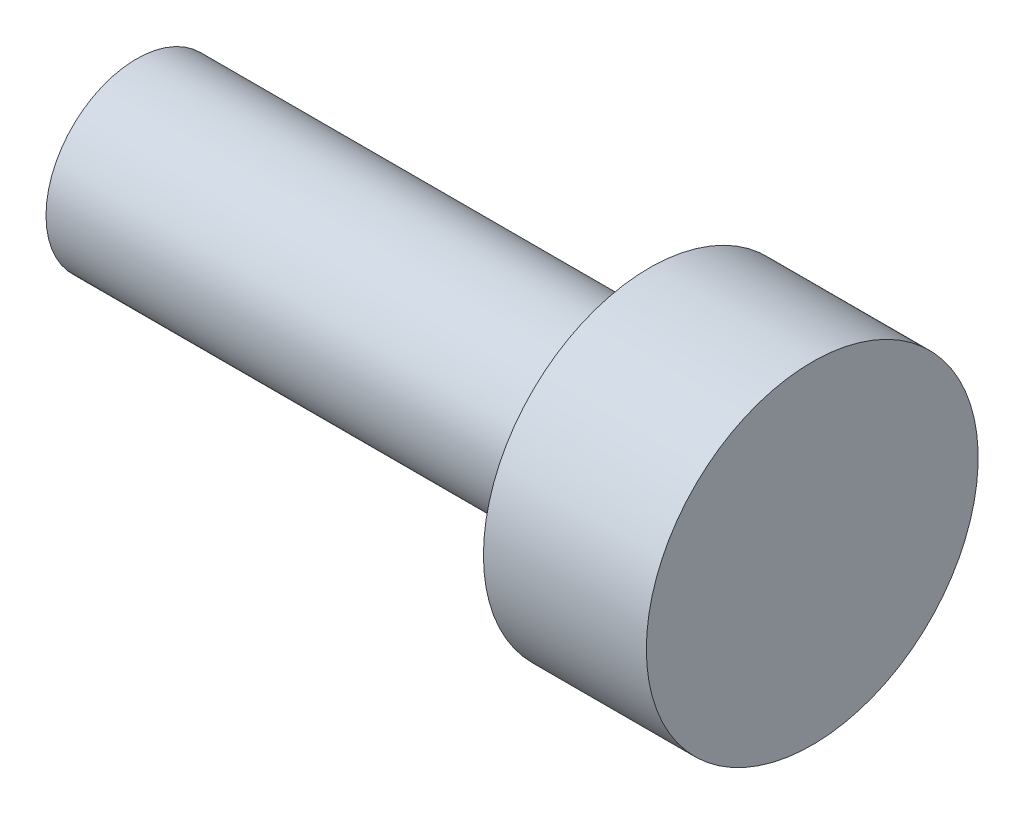
SolidWorks part; units mm, degrees
material "AISI Type 316L stainless steel"
ref_plane "Front Plane" through (0, 0, 0) normal (0, 0, 1) x (1, 0, 0)
ref_plane "Top Plane" through (0, 0, 0) normal (0, 1, 0) x (1, 0, 0)
ref_plane "Right Plane" through (0, 0, 0) normal (1, 0, 0) x (0, 0, -1)
sketch "Axial profile (mm)" plane through (0, 0, 0) normal (0, 0, 1) x (1, 0, 0)
  line L0 (-110, 0) -> (75, 0) construction
  line L1 (165.5, 0) -> (176.7, 0)
  line L2 (176.7, 0) -> (176.7, 2.75)
  line L3 (176.7, 2.75) -> (174, 2.75)
  line L4 (174, 2.75) -> (174, 1.5)
  line L5 (174, 1.5) -> (165.5, 1.5)
  line L6 (165.5, 1.5) -> (165.5, 0)
revolve "Full revolution" add sketch "Axial profile (mm)" angle 360 about L0
